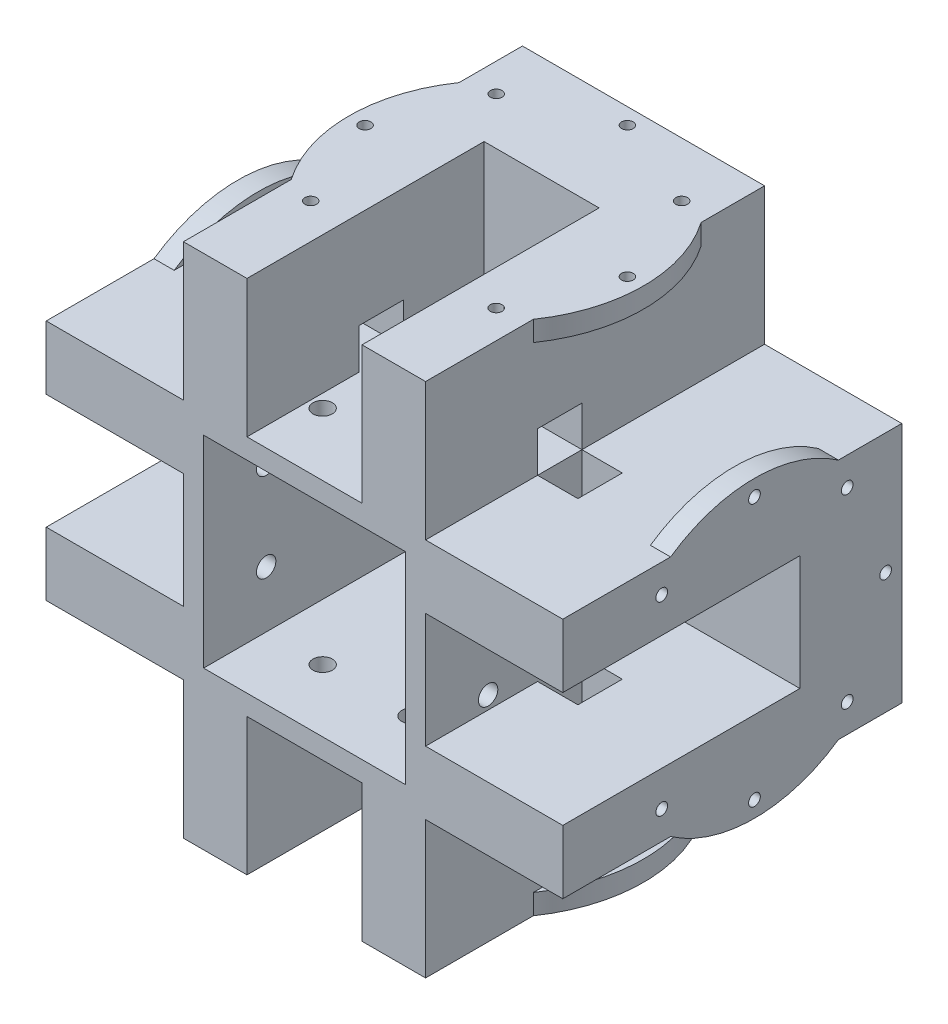
SolidWorks part; units mm, degrees
ref_plane "前视基准面" through (0, 0, 0) normal (0, 0, 1) x (1, 0, 0)
ref_plane "上视基准面" through (0, 0, 0) normal (0, 1, 0) x (1, 0, 0)
ref_plane "右视基准面" through (0, 0, 0) normal (1, 0, 0) x (0, 0, -1)
sketch "草图1" plane through (0, 0, 0) normal (0, 0, 1) x (1, 0, 0)
  line L1 (-95.8696, 54.8587) -> (-35.8696, 54.8587)
  line L2 (-95.8696, 54.8587) -> (-95.8696, -5.1413)
  line L3 (-95.8696, -5.1413) -> (-35.8696, -5.1413)
  line L4 (-35.8696, 54.8587) -> (-35.8696, -5.1413)
  dimension "D1" = 60
  dimension "D2" = 60
extrude "拉伸-薄壁1" add sketch "草图1" along normal blind 84 thin
sketch "草图5" plane through (-35.8696, 0, 0) normal (1, 0, 0) x (0, 0, -1)
  line L0 (-84, -5.1413) -> (0, -5.1413) construction
  line L1 (0, 54.8587) -> (-5, 54.8587)
  line L2 (0, 54.8587) -> (0, -5.1413)
  line L3 (0, -5.1413) -> (-5, -5.1413)
  line L4 (-5, 39.1087) -> (-5, 10.6087)
  line L6 (-84, -5.1413) -> (-84, 54.8587) construction
  line L7 (-84, 54.8587) -> (-5, 54.8587)
  line L8 (-84, 54.8587) -> (-84, 39.1087)
  line L9 (-84, 39.1087) -> (-5, 39.1087)
  line L11 (-84, 10.6087) -> (-5, 10.6087)
  line L12 (-84, 10.6087) -> (-84, -5.1413)
  line L13 (-84, -5.1413) -> (-5, -5.1413)
  dimension "D1" = 5
  dimension "D2" = 15.75
  dimension "D3" = 15.75
extrude "凸台-拉伸2" add sketch "草图5" along normal blind 34
sketch "草图8" plane through (0, 54.8587, 0) normal (0, 1, 0) x (1, 0, 0)
  line L0 (-1.8696, -84) -> (-95.8696, -84) construction
  line L1 (-95.8696, 0) -> (-35.8696, 0)
  line L2 (-95.8696, 0) -> (-95.8696, -5)
  line L3 (-80.1196, -5) -> (-51.6196, -5)
  line L4 (-35.8696, 0) -> (-35.8696, -5)
  line L6 (-95.8696, -5) -> (-95.8696, -84)
  line L7 (-95.8696, -84) -> (-80.1196, -84)
  line L8 (-80.1196, -5) -> (-80.1196, -84)
  line L15 (-35.8696, -5) -> (-35.8696, -84)
  line L16 (-35.8696, -84) -> (-51.6196, -84)
  line L17 (-51.6196, -5) -> (-51.6196, -84)
  dimension "D1" = 5
  dimension "D2" = 60
  dimension "D3" = 15.75
  dimension "D4" = 15.75
extrude "凸台-拉伸5" add sketch "草图8" along normal blind 34
sketch "草图9" plane through (-95.8696, 0, 0) normal (-1, 0, 0) x (0, 0, 1)
  line L0 (84, 88.8587) -> (84, -5.1413) construction
  line L1 (0, -5.1413) -> (5, -5.1413)
  line L2 (0, -5.1413) -> (0, 54.8587)
  line L3 (0, 54.8587) -> (5, 54.8587)
  line L4 (5, 10.6087) -> (5, 39.1087)
  line L5 (5, -5.1413) -> (84, -5.1413)
  line L7 (5, 10.6087) -> (84, 10.6087)
  line L8 (84, -5.1413) -> (84, 10.6087)
  line L10 (5, 54.8587) -> (84, 54.8587)
  line L12 (5, 39.1087) -> (84, 39.1087)
  line L13 (84, 54.8587) -> (84, 39.1087)
  dimension "D1" = 5
  dimension "D2" = 60
  dimension "D3" = 15.75
  dimension "D4" = 15.75
extrude "凸台-拉伸6" add sketch "草图9" along normal blind 34
sketch "草图10" plane through (0, -5.1413, 0) normal (0, -1, 0) x (-1, 0, 0)
  line L0 (129.8696, 0) -> (1.8696, 0) construction
  line L1 (95.8696, 0) -> (35.8696, 0)
  line L2 (95.8696, 0) -> (95.8696, -6.6582)
  line L3 (80.1196, -6.6582) -> (51.6196, -6.6582)
  line L4 (35.8696, 0) -> (35.8696, -6.6582)
  line L5 (129.8696, 0) -> (129.8696, -84) construction
  line L7 (1.8696, -84) -> (1.8696, 0) construction
  line L8 (129.8696, -84) -> (1.8696, -84) construction
  line L10 (95.8696, -6.6582) -> (95.8696, -84)
  line L11 (95.8696, -84) -> (80.1196, -84)
  line L12 (80.1196, -6.6582) -> (80.1196, -84)
  line L15 (35.8696, -6.6582) -> (35.8696, -84)
  line L16 (35.8696, -84) -> (51.6196, -84)
  line L17 (51.6196, -6.6582) -> (51.6196, -84)
  dimension "D1" = 34
  dimension "D2" = 34
  dimension "D3" = 15.75
  dimension "D4" = 15.75
extrude "凸台-拉伸7" add sketch "草图10" along normal blind 34
sketch "草图12" plane through (-129.8696, 0, 0) normal (-1, 0, 0) x (0, 0, 1)
  line L0 (0, -5.1413) -> (84, -5.1413) construction
  line L1 (0, 54.8587) -> (0, -5.1413) construction
  circle A0 centre (36.5, 24.8587) radius 36.5
  dimension "D1" = 73
  dimension "D2" = 30
  dimension "D3" = 36.5
extrude "凸台-拉伸8" add sketch "草图12" against normal blind 5
sketch "草图13" plane through (-1.8696, 0, 0) normal (1, 0, 0) x (0, 0, -1)
  line L0 (-84, -5.1413) -> (0, -5.1413) construction
  line L1 (0, -5.1413) -> (0, 54.8587) construction
  circle A0 centre (-36.5, 24.8587) radius 36.5
  dimension "D1" = 73
  dimension "D2" = 30
  dimension "D3" = 36.5
extrude "凸台-拉伸9" add sketch "草图13" against normal blind 5
sketch "草图14" plane through (0, 88.8587, 0) normal (0, 1, 0) x (1, 0, 0)
  line L0 (-35.8696, -84) -> (-35.8696, 0) construction
  line L1 (-35.8696, 0) -> (-95.8696, 0) construction
  circle A0 centre (-65.8696, -36.5) radius 36.5
  dimension "D1" = 73
  dimension "D2" = 30
  dimension "D3" = 36.5
extrude "凸台-拉伸10" add sketch "草图14" against normal blind 5
sketch "草图15" plane through (0, -39.1413, 0) normal (0, -1, 0) x (-1, 0, 0)
  line L0 (95.8696, 0) -> (35.8696, 0) construction
  line L1 (35.8696, 0) -> (35.8696, -84) construction
  circle A0 centre (65.8696, -36.5) radius 36.5
  dimension "D1" = 36.5
  dimension "D2" = 73
  dimension "D3" = 30
extrude "凸台-拉伸11" add sketch "草图15" against normal blind 5
sketch "草图22" plane through (0, 0, 5) normal (0, 0, 1) x (1, 0, 0)
  line L1 (-95.8696, 39.1087) -> (-124.8696, 39.1087)
  line L2 (-95.8696, 39.1087) -> (-95.8696, 10.6087)
  line L3 (-95.8696, 10.6087) -> (-124.8696, 10.6087)
  line L4 (-124.8696, 39.1087) -> (-124.8696, 10.6087)
  line L5 (-80.1196, 83.8587) -> (-51.6196, 83.8587)
  line L6 (-80.1196, 83.8587) -> (-80.1196, 54.8587)
  line L7 (-80.1196, 54.8587) -> (-51.6196, 54.8587)
  line L8 (-51.6196, 83.8587) -> (-51.6196, 54.8587)
  line L9 (-35.8696, 39.1087) -> (-6.8696, 39.1087)
  line L10 (-35.8696, 39.1087) -> (-35.8696, 10.6087)
  line L11 (-35.8696, 10.6087) -> (-6.8696, 10.6087)
  line L12 (-6.8696, 39.1087) -> (-6.8696, 10.6087)
  line L13 (-80.1196, -34.1413) -> (-51.6196, -34.1413)
  line L14 (-80.1196, -34.1413) -> (-80.1196, -5.1413)
  line L15 (-80.1196, -5.1413) -> (-51.6196, -5.1413)
  line L16 (-51.6196, -34.1413) -> (-51.6196, -5.1413)
extrude "凸台-拉伸12" add sketch "草图22" along normal blind 60
sketch "草图18" plane through (0, 88.8587, 0) normal (0, 1, 0) x (1, 0, 0)
  circle A0 centre (-98.3696, -36.5) radius 1.45
  arc A1 (-80.1196, -70.1034) -> (-51.6196, -70.1034) centre (-65.8696, -36.5) ccw construction
  dimension "D1" = 2.9
  dimension "D2" = 0
  dimension "D3" = 32.5
extrude "切除-拉伸2" cut sketch "草图18" against normal blind 5
pattern_circular "阵列(圆周)1" count 8 over 360 about axis through (-65.8696, 0, 36.5) along (0, 1, 0) of "切除-拉伸2"
sketch "草图19" plane through (-1.8696, 0, 0) normal (1, 0, 0) x (0, 0, -1)
  circle A0 centre (-36.5, 57.3587) radius 1.45
  arc A1 (-70.1034, 39.1087) -> (-70.1034, 10.6087) centre (-36.5, 24.8587) ccw construction
  dimension "D1" = 2.9
  dimension "D2" = 0
  dimension "D3" = 32.5
extrude "切除-拉伸3" cut sketch "草图19" against normal blind 5
pattern_circular "阵列(圆周)2" count 8 over 360 about axis through (0, 24.8587, 36.5) along (1, 0, 0) of "切除-拉伸3"
sketch "草图20" plane through (0, -39.1413, 0) normal (0, -1, 0) x (-1, 0, 0)
  circle A0 centre (98.3696, -36.5) radius 1.45
  arc A1 (95.8696, -57.2906) -> (95.8696, -15.7094) centre (65.8696, -36.5) ccw construction
  arc A2 (35.8696, -15.7094) -> (35.8696, -57.2906) centre (65.8696, -36.5) ccw construction
  dimension "D1" = 2.9
  dimension "D2" = 0
  dimension "D3" = 32.5
extrude "切除-拉伸4" cut sketch "草图20" against normal blind 5
pattern_circular "阵列(圆周)3" count 8 over 360 about axis through (-65.8696, 0, 36.5) along (0, 1, 0) of "切除-拉伸4"
sketch "草图21" plane through (-129.8696, 0, 0) normal (-1, 0, 0) x (0, 0, 1)
  circle A0 centre (36.5, 57.3587) radius 1.45
  arc A1 (57.2906, 54.8587) -> (15.7094, 54.8587) centre (36.5, 24.8587) ccw construction
  dimension "D1" = 2.9
  dimension "D2" = 0
  dimension "D3" = 32.5
extrude "切除-拉伸5" cut sketch "草图21" against normal blind 5
pattern_circular "阵列(圆周)4" count 8 over 360 about axis through (0, 24.8587, 36.5) along (1, 0, 0) of "切除-拉伸5"
sketch "草图26" plane through (0, 0, 84) normal (0, 0, 1) x (1, 0, 0)
  line L1 (-129.8696, 39.1087) -> (-95.8696, 39.1087)
  line L2 (-129.8696, 39.1087) -> (-129.8696, 10.6087)
  line L3 (-129.8696, 10.6087) -> (-95.8696, 10.6087)
  line L4 (-95.8696, 39.1087) -> (-95.8696, 10.6087)
  line L5 (-80.1196, 88.8587) -> (-51.6196, 88.8587)
  line L6 (-80.1196, 88.8587) -> (-80.1196, 54.8587)
  line L7 (-80.1196, 54.8587) -> (-51.6196, 54.8587)
  line L8 (-51.6196, 88.8587) -> (-51.6196, 54.8587)
  line L9 (-35.8696, 39.1087) -> (-1.8696, 39.1087)
  line L10 (-35.8696, 39.1087) -> (-35.8696, 10.6087)
  line L11 (-35.8696, 10.6087) -> (-1.8696, 10.6087)
  line L12 (-1.8696, 39.1087) -> (-1.8696, 10.6087)
  line L13 (-80.1196, -5.1413) -> (-51.6196, -5.1413)
  line L14 (-80.1196, -5.1413) -> (-80.1196, -39.1413)
  line L15 (-80.1196, -39.1413) -> (-51.6196, -39.1413)
  line L16 (-51.6196, -5.1413) -> (-51.6196, -39.1413)
extrude "切除-拉伸7" cut sketch "草图26" against normal blind 58.75
sketch "草图27" plane through (-129.8696, 0, 0) normal (-1, 0, 0) x (0, 0, 1)
  circle A0 centre (36.5, 24.8587) radius 10.5
extrude "切除-拉伸8" cut sketch "草图27" against normal blind 200
sketch "草图28" plane through (0, 88.8587, 0) normal (0, 1, 0) x (1, 0, 0)
  circle A0 centre (-65.8696, -36.5) radius 10.5
extrude "切除-拉伸9" cut sketch "草图28" against normal blind 200
sketch "草图31" plane through (-95.8696, 0, 0) normal (-1, 0, 0) x (0, 0, 1)
  line L0 (25.25, 39.1087) -> (25.25, 10.6087) construction
  line L1 (84, 10.6087) -> (25.25, 10.6087) construction
  line L2 (25.25, 39.1087) -> (84, 39.1087) construction
  line L4 (84, 10.6087) -> (25.25, 10.6087) construction
  circle A0 centre (28.5, 13.8587) radius 2.4
  circle A1 centre (28.5, 35.8587) radius 2.4
  circle A2 centre (68.5, 35.8587) radius 2.4
  circle A3 centre (68.5, 13.8587) radius 2.4
  dimension "D1" = 3.25
  dimension "D3" = 3.25
  dimension "D5" = 3.25
  dimension "D6" = 40
  dimension "D7" = 3.25
  dimension "D2" = 3.25
  dimension "D4" = 3.25
  dimension "D8" = 40
extrude "切除-拉伸12" cut sketch "草图31" against normal blind 200
sketch "草图32" plane through (0, -5.1413, 0) normal (0, -1, 0) x (-1, 0, 0)
  line L0 (51.6196, -25.25) -> (80.1196, -25.25) construction
  line L1 (80.1196, -25.25) -> (80.1196, -84) construction
  line L2 (80.1196, -25.25) -> (51.6196, -25.25) construction
  line L3 (51.6196, -84) -> (51.6196, -25.25) construction
  line L4 (51.6196, -84) -> (51.6196, -25.25) construction
  circle A0 centre (76.8696, -28.5) radius 2.4
  circle A1 centre (54.8696, -28.5) radius 2.4
  circle A2 centre (54.8696, -68.5) radius 2.4
  circle A3 centre (76.8696, -68.5) radius 2.4
  dimension "D1" = 3.25
  dimension "D2" = 3.25
  dimension "D3" = 3.25
  dimension "D4" = 3.25
  dimension "D5" = 3.25
  dimension "D6" = 40
  dimension "D7" = 3.25
  dimension "D8" = 40
extrude "切除-拉伸13" cut sketch "草图32" against normal blind 200
sketch "草图33" plane through (-51.6196, 0, 0) normal (-1, 0, 0) x (0, 0, 1)
  line L0 (84, -5.1413) -> (25.25, -5.1413) construction
  line L1 (45.25, -5.1413) -> (56.25, -5.1413)
  line L2 (45.25, -5.1413) -> (45.25, -15.1413)
  line L3 (45.25, -15.1413) -> (56.25, -15.1413)
  line L4 (56.25, -5.1413) -> (56.25, -15.1413)
  line L5 (25.25, -39.1413) -> (25.25, -5.1413) construction
  dimension "D1" = 20
  dimension "D2" = 11
  dimension "D3" = 10
extrude "切除-拉伸14" cut sketch "草图33" against normal blind 40 and the other way blind 50
sketch "草图34" plane through (0, 10.6087, 0) normal (0, 1, 0) x (1, 0, 0)
  line L0 (-95.8696, -84) -> (-95.8696, -25.25) construction
  line L1 (-95.8696, -45.25) -> (-105.8696, -45.25)
  line L2 (-95.8696, -45.25) -> (-95.8696, -56.25)
  line L3 (-95.8696, -56.25) -> (-105.8696, -56.25)
  line L4 (-105.8696, -45.25) -> (-105.8696, -56.25)
  line L5 (-129.8696, -25.25) -> (-95.8696, -25.25) construction
  dimension "D1" = 20
  dimension "D2" = 11
  dimension "D3" = 10
extrude "切除-拉伸15" cut sketch "草图34" against normal blind 40 and the other way blind 60
sketch "草图35" plane through (-95.8696, 0, 0) normal (-1, 0, 0) x (0, 0, 1)
  line L0 (25.25, 88.8587) -> (25.25, 54.8587) construction
  line L1 (56.25, 54.8587) -> (45.25, 54.8587)
  line L2 (56.25, 54.8587) -> (56.25, 64.8587)
  line L3 (56.25, 64.8587) -> (45.25, 64.8587)
  line L4 (45.25, 54.8587) -> (45.25, 64.8587)
  dimension "D1" = 20
  dimension "D2" = 10
extrude "切除-拉伸16" cut sketch "草图35" against normal blind 80
sketch "草图36" plane through (0, 54.8587, 0) normal (0, 1, 0) x (1, 0, 0)
  line L1 (-35.8696, -45.25) -> (-25.8696, -45.25)
  line L2 (-35.8696, -45.25) -> (-35.8696, -56.25)
  line L3 (-35.8696, -56.25) -> (-25.8696, -56.25)
  line L4 (-25.8696, -45.25) -> (-25.8696, -56.25)
  dimension "D1" = 11
  dimension "D2" = 10
extrude "切除-拉伸17" cut sketch "草图36" against normal blind 80
